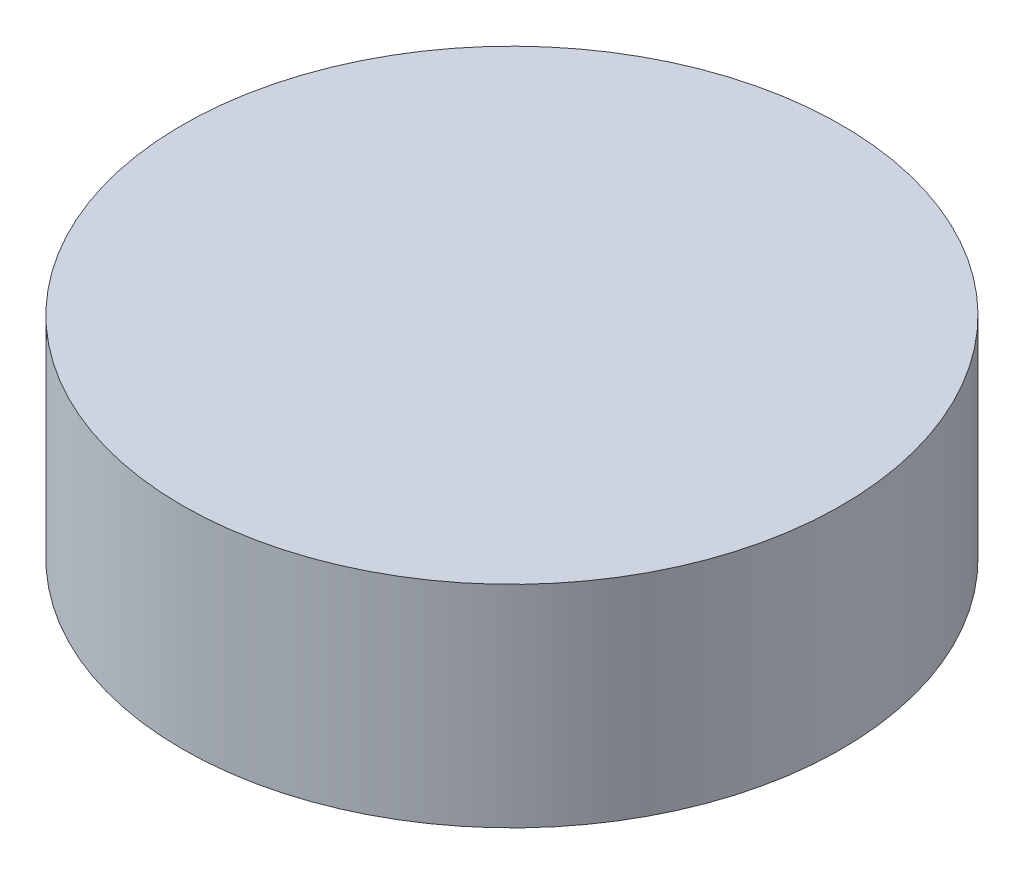
SolidWorks part; units mm, degrees
ref_plane "Plan de face" through (0, 0, 0) normal (0, 0, 1) x (1, 0, 0)
ref_plane "Plan de dessus" through (0, 0, 0) normal (0, 1, 0) x (1, 0, 0)
ref_plane "Plan de droite" through (0, 0, 0) normal (1, 0, 0) x (0, 0, -1)
sketch "Esquisse1" plane through (0, 0, 0) normal (0, 1, 0) x (1, 0, 0)
  circle A0 centre (0, 0) radius 37.5
extrude "Boss.-Extru.1" add sketch "Esquisse1" along normal blind 24
